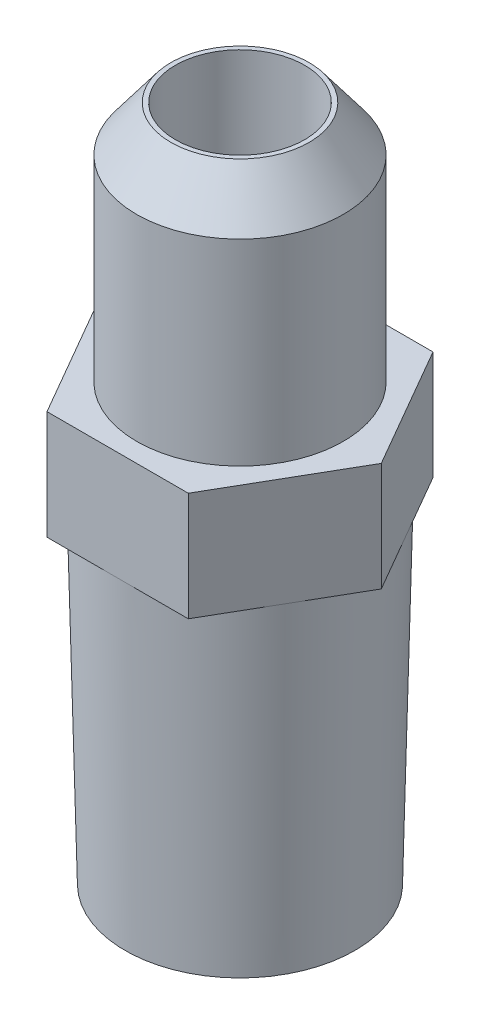
SolidWorks part; units mm, degrees
material "6061-T6 (SS)"
ref_plane "Front Plane" through (0, 0, 0) normal (0, 0, 1) x (1, 0, 0)
ref_plane "Top Plane" through (0, 0, 0) normal (0, 1, 0) x (1, 0, 0)
ref_plane "Right Plane" through (0, 0, 0) normal (1, 0, 0) x (0, 0, -1)
sketch "Sketch1" plane through (0, 0, 0) normal (0, 1, 0) x (1, 0, 0)
  line L1 (-8.2489, 0) -> (-4.1244, -7.1437)
  line L2 (-4.1244, -7.1437) -> (4.1244, -7.1438)
  line L3 (4.1244, -7.1438) -> (8.2489, 0)
  line L4 (8.2489, 0) -> (4.1244, 7.1438)
  line L5 (4.1244, 7.1438) -> (-4.1244, 7.1438)
  line L6 (-4.1244, 7.1438) -> (-8.2489, 0)
  circle A0 centre (0, 0) radius 7.1438 construction
  point P1 (0, 0)
  point P10 (0, 0)
  dimension "D1" = 14.2875
extrude "Boss-Extrude1" add sketch "Sketch1" along normal blind 6.35
sketch "Sketch2" plane through (0, 6.35, 0) normal (0, 1, 0) x (1, 0, 0)
  circle A0 centre (0, 0) radius 6.0325
  dimension "D1" = 12.065
extrude "Boss-Extrude2" add sketch "Sketch2" along normal blind 14.1224
sketch "Sketch3" plane through (0, 20.4724, 0) normal (0, 1, 0) x (1, 0, 0)
  circle A0 centre (0, 0) radius 4.0386
  circle A1 centre (0, 0) radius 16.1845
  dimension "D1" = 8.0772
extrude "Cut-Extrude1" cut sketch "Sketch3" against normal through all draft 37
sketch "Sketch6" plane through (0, 0, 0) normal (0, -1, 0) x (1, 0, 0)
  line L0 (-4.1244, -7.1438) -> (-8.2489, 0) construction
  circle A0 centre (0, 0) radius 7.1438
extrude "Boss-Extrude3" add sketch "Sketch6" along normal blind 19.05 draft 1.3
sketch "Sketch4" plane through (0, 20.4724, 0) normal (0, 1, 0) x (1, 0, 0)
  circle A0 centre (0, 0) radius 3.7719
  dimension "D1" = 7.5438
extrude "Cut-Extrude2" cut sketch "Sketch4" against normal through all
